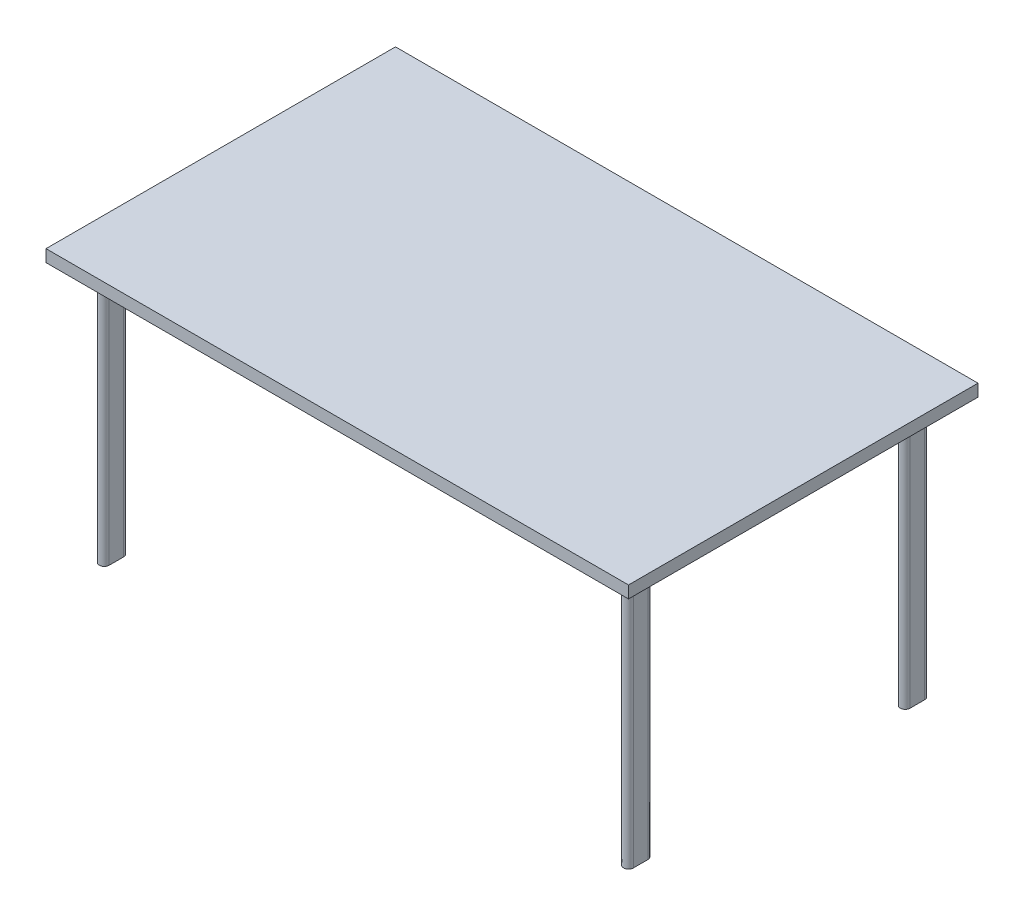
SolidWorks part; units mm, degrees
ref_plane "Front Plane" through (0, 0, 0) normal (0, 0, 1) x (1, 0, 0)
ref_plane "Top Plane" through (0, 0, 0) normal (0, 1, 0) x (1, 0, 0)
ref_plane "Right Plane" through (0, 0, 0) normal (1, 0, 0) x (0, 0, -1)
sketch "Sketch1" plane through (0, 0, 0) normal (0, 1, 0) x (1, 0, 0)
  line L1 (-762, -457.2) -> (762, -457.2)
  line L2 (-762, -457.2) -> (-762, 457.2)
  line L3 (-762, 457.2) -> (762, 457.2)
  line L4 (762, -457.2) -> (762, 457.2)
  line L5 (-762, -457.2) -> (762, 457.2) construction
  line L6 (-762, 457.2) -> (762, -457.2) construction
  point P0 (0, 0)
  dimension "D1" = 1524
  dimension "D2" = 914.4
extrude "Boss-Extrude1" add sketch "Sketch1" against normal blind 31.75
sketch "Sketch2" plane through (0, -31.75, 0) normal (0, -1, 0) x (1, 0, 0)
  line L0 (-698.5, -342.9) -> (-698.5, -381)
  line L1 (-698.5, 381) -> (-698.5, 342.9)
  line L2 (-673.1, 381) -> (-673.1, 342.9)
  line L3 (-673.1, -342.9) -> (-673.1, -381)
  line L4 (673.1, 381) -> (673.1, 342.9)
  line L5 (698.5, 381) -> (698.5, 342.9)
  line L6 (673.1, -342.9) -> (673.1, -381)
  line L7 (698.5, -342.9) -> (698.5, -381)
  line L8 (-762, 457.2) -> (762, 457.2) construction
  line L9 (-762, -457.2) -> (-762, 457.2) construction
  line L12 (762, 457.2) -> (762, -457.2) construction
  line L13 (762, -457.2) -> (-762, -457.2) construction
  arc A0 (-673.1, 381) -> (-698.5, 381) centre (-685.8, 381) ccw
  arc A1 (-698.5, 342.9) -> (-673.1, 342.9) centre (-685.8, 342.9) ccw
  arc A2 (-673.1, -342.9) -> (-698.5, -342.9) centre (-685.8, -342.9) ccw
  arc A3 (-698.5, -381) -> (-673.1, -381) centre (-685.8, -381) ccw
  arc A4 (698.5, 381) -> (673.1, 381) centre (685.8, 381) ccw
  arc A5 (673.1, 342.9) -> (698.5, 342.9) centre (685.8, 342.9) ccw
  arc A6 (698.5, -342.9) -> (673.1, -342.9) centre (685.8, -342.9) ccw
  arc A7 (673.1, -381) -> (698.5, -381) centre (685.8, -381) ccw
  dimension "D1" = 76.2
  dimension "D2" = 76.2
  dimension "D4" = 12.7
  dimension "D5" = 38.1
  dimension "D6" = 12.7
  dimension "D8" = 12.7
  dimension "D10" = 12.7
  dimension "D3" = 38.1
  dimension "D7" = 38.1
  dimension "D9" = 38.1
  dimension "D11" = 76.2
  dimension "D12" = 76.2
  dimension "D13" = 76.2
  dimension "D14" = 76.2
  dimension "D15" = 76.2
  dimension "D16" = 76.2
extrude "Boss-Extrude2" add sketch "Sketch2" along normal blind 679.45
